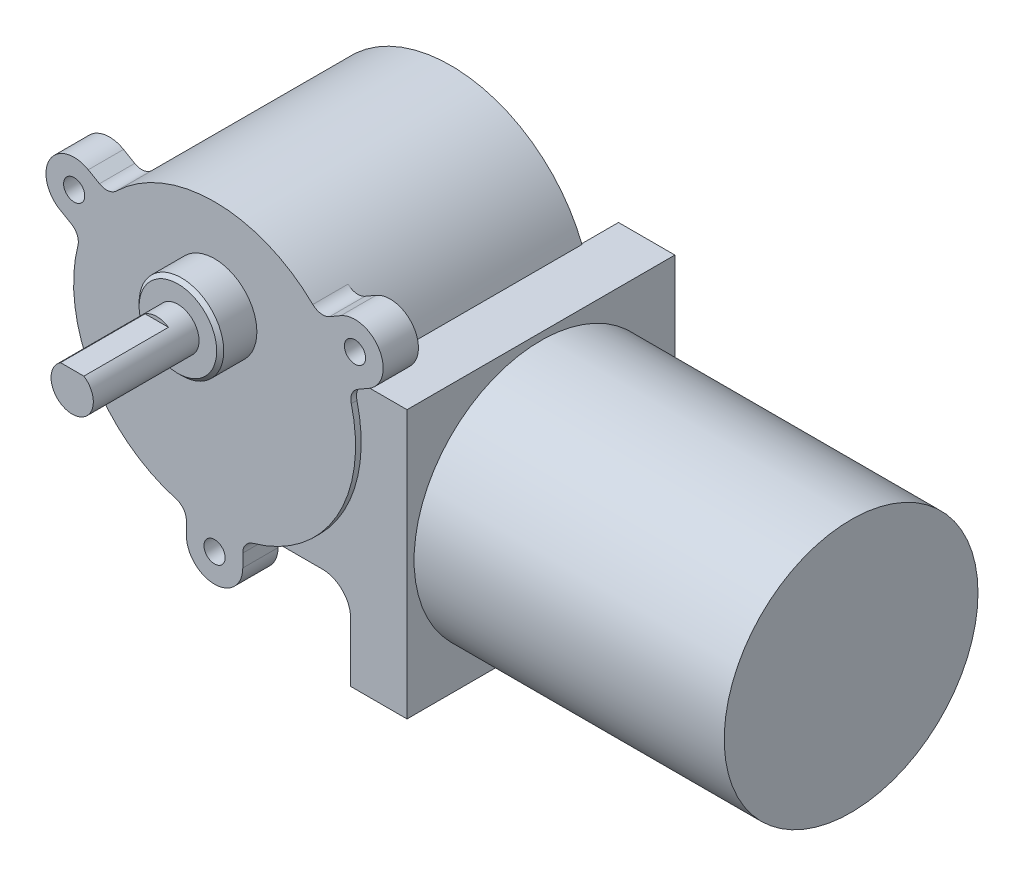
SolidWorks part; units mm, degrees
ref_plane "正面" through (0, 0, 0) normal (0, 0, 1) x (1, 0, 0)
ref_plane "平面" through (0, 0, 0) normal (0, 1, 0) x (1, 0, 0)
ref_plane "右側面" through (0, 0, 0) normal (1, 0, 0) x (0, 0, -1)
sketch "ｽｹｯﾁ1" plane through (0, 0, 0) normal (0, 0, 1) x (1, 0, 0)
  circle A0 centre (0, 0) radius 6
  dimension "D1" = 12
extrude "ﾎﾞｽ - 押し出し1" add sketch "ｽｹｯﾁ1" along normal blind 5.2
chamfer "面取り1" distance 0.5 angle 45 1 edges at (6, 0, 5.2)
sketch "ｽｹｯﾁ2" plane through (0, 0, 5.2) normal (0, 0, 1) x (1, 0, 0)
  circle A0 centre (0, 0) radius 3
  dimension "D1" = 6
extrude "ﾎﾞｽ - 押し出し2" add sketch "ｽｹｯﾁ2" along normal blind 15
sketch "ｽｹｯﾁ3" plane through (0, 0, 20.2) normal (0, 0, 1) x (1, 0, 0)
  line L0 (-1.6583, 2.5) -> (1.6583, 2.5)
  arc A0 (-1.6583, 2.5) -> (1.6583, 2.5) centre (0, 0) ccw
  circle A1 centre (0, 0) radius 3 construction
  dimension "D1" = 2.5
extrude "ｶｯﾄ - 押し出し1" cut sketch "ｽｹｯﾁ3" against normal blind 12 flip side to cut
sketch "ｽｹｯﾁ4" plane through (0, 0, 0) normal (0, 0, -1) x (-1, 0, 0)
  circle A0 centre (0, -7) radius 20
  point P2 (0, 0)
  dimension "D1" = 40
  dimension "D2" = 7
extrude "ﾎﾞｽ - 押し出し3" add sketch "ｽｹｯﾁ4" along normal blind 33.5
sketch "ｽｹｯﾁ5" plane through (0, 0, 0) normal (0, 0, 1) x (1, 0, 0)
  line L0 (-4, -26.5959) -> (-4, -30)
  line L1 (4, -26.5959) -> (4, -30)
  line L2 (-4, -26.5959) -> (4, -26.5959)
  circle A0 centre (0, -7) radius 20 construction
  arc A2 (-4, -30) -> (4, -30) centre (0, -30) ccw
  circle A3 centre (0, -30) radius 1.5
  dimension "D3" = 3
  dimension "D1" = 8
  dimension "D2" = 23
extrude "ﾎﾞｽ - 押し出し4" add sketch "ｽｹｯﾁ5" against normal blind 5
fillet "ﾌｨﾚｯﾄ2" radius 2 2 edges at (4, -26.5959, -2.5) (-4, -26.5959, -2.5)
pattern_circular "円形ﾊﾟﾀｰﾝ1" count 3 over 360 about axis through (0, -7, 0) along (0, 0, 1) of "ﾎﾞｽ - 押し出し4", "ﾌｨﾚｯﾄ2"
ref_plane "平面1" through (26.5, 0, 0) normal (1, 0, 0) x (0, 0, -1)
sketch "ｽｹｯﾁ7" plane through (26.5, 0, 0) normal (1, 0, 0) x (0, 0, -1)
  line L0 (0, 13) -> (0, -27) construction
  line L1 (0.8, -37.7) -> (38.8, -37.7)
  line L2 (0.8, -37.7) -> (0.8, 0.3)
  line L3 (0.8, 0.3) -> (38.8, 0.3)
  line L4 (38.8, -37.7) -> (38.8, 0.3)
  line L5 (0.8, -37.7) -> (38.8, 0.3) construction
  line L6 (0.8, 0.3) -> (38.8, -37.7) construction
  point P0 (19.8, -18.7)
  dimension "D1" = 38
  dimension "D2" = 19.8
  dimension "D3" = 18.7
extrude "ﾎﾞｽ - 押し出し5" add sketch "ｽｹｯﾁ7" against normal blind 8
sketch "ｽｹｯﾁ8" plane through (18.5, 0, 0) normal (-1, 0, 0) x (0, 0, 1)
  line L0 (-38.8, 0.3) -> (-33.5, 0.3) construction
  line L1 (-0.8, 0.3) -> (-33.5, 0.3)
  line L2 (-0.8, 0.3) -> (-0.8, -25.3)
  line L3 (-0.8, -25.3) -> (-33.5, -25.3)
  line L4 (-33.5, 0.3) -> (-33.5, -25.3)
  line L5 (-0.8, 0.3) -> (-33.5, -25.3) construction
  line L6 (-0.8, -25.3) -> (-33.5, 0.3) construction
  line L7 (-0.8, -14.5993) -> (-0.8, -37.7) construction
  line L8 (-33.5, 13) -> (-33.5, -27) construction
  line L9 (-0.8, -37.7) -> (-38.8, -37.7) construction
  point P4 (-17.15, -12.5)
  point P9 (-27.2365, -22.9316)
  dimension "D1" = 12.4
extrude "ﾎﾞｽ - 押し出し6" add sketch "ｽｹｯﾁ8" along normal up to next
sketch "ｽｹｯﾁ10" plane through (26.5, 0, 0) normal (1, 0, 0) x (0, 0, -1)
  line L0 (0.8, 0.3) -> (38.8, -37.7) construction
  line L1 (0.8, -37.7) -> (38.8, 0.3) construction
  circle A0 centre (19.8, -18.7) radius 18
  dimension "D1" = 36
extrude "ﾎﾞｽ - 押し出し7" add sketch "ｽｹｯﾁ10" along normal blind 44
fillet "ﾌｨﾚｯﾄ1" radius 4 1 edges at (18.5, -25.3, -17.15)
